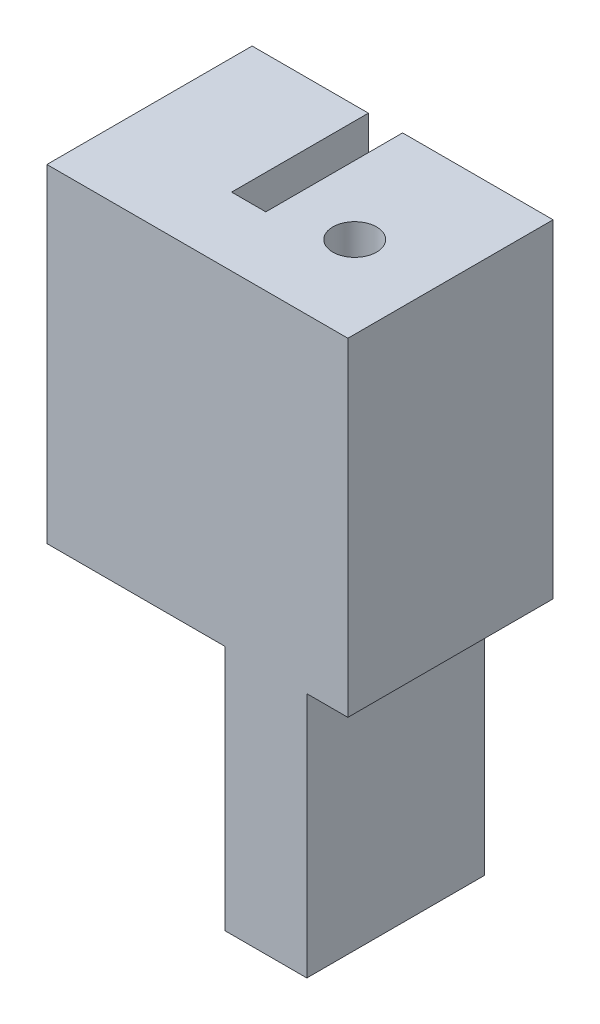
SolidWorks part; units mm, degrees
material "PET"
ref_plane "Front Plane" through (0, 0, 0) normal (0, 0, 1) x (1, 0, 0)
ref_plane "Top Plane" through (0, 0, 0) normal (0, 1, 0) x (1, 0, 0)
ref_plane "Right Plane" through (0, 0, 0) normal (1, 0, 0) x (0, 0, -1)
sketch "Sketch2" plane through (0, 0, 0) normal (0, 0, 1) x (1, 0, 0)
  line L0 (-26.5, 0) -> (-30.65, 0)
  line L1 (-26.5, 24) -> (-28.5, 24)
  line L2 (-26.5, 24) -> (-26.5, 0)
  line L4 (-28.5, 24) -> (-28.5, 6.0276)
  line L5 (-31, 24) -> (-39.5, 24)
  line L6 (-31, 24) -> (-31, 13.19)
  line L7 (-30.2, 5.5304) -> (-30.2, 11.6897)
  line L8 (-39.5, 24) -> (-39.5, 8.68)
  line L9 (-30.2, 11.6897) -> (-35.6851, 8.8877)
  line L10 (-31, 13.19) -> (-36.71, 10.2731)
  line L11 (-38.4927, 8.4496) -> (-39.5, 6.3626)
  line L12 (-39.5, 6.3626) -> (-39.5, 8.68)
  line L13 (-31.0158, 1.1429) -> (-32.6182, 0)
  line L14 (-32.6182, 0) -> (-30.65, 0)
  arc A1 (-31.0158, 1.1429) -> (-28.5, 6.0276) centre (-34.5, 6.0276) ccw
  arc A3 (-36.71, 10.2731) -> (-38.4927, 8.4496) centre (-34.8903, 6.711) ccw
  arc A4 (-35.6851, 8.8877) -> (-30.2, 5.5304) centre (-33.97, 5.5304) ccw
  dimension "D4" = 35.499
  dimension "D5" = 12
  dimension "D10" = 25.764
  dimension "D13" = 8
  dimension "D12" = 7.54
  dimension "D1" = 2
  dimension "D2" = 24
  dimension "D3" = 4.15
  dimension "D6" = 8.5
  dimension "D7" = 10.81
  dimension "D8" = 2.5
  dimension "D9" = 15.32
  dimension "D11" = 5.71
  dimension "D14" = 1.7
  dimension "D15" = 1.7
  dimension "D16" = 2.3174
  dimension "D17" = 1.9682
extrude "Boss-Extrude1" add sketch "Sketch2" along normal blind 10
sketch "Sketch3" plane through (0, 0, 10) normal (0, 0, 1) x (1, 0, 0)
  line L0 (-32.6182, 0) -> (-26.5, 0) construction
  line L1 (-26.5, 24) -> (-39.5, 24)
  line L2 (-26.5, 24) -> (-26.5, 0)
  line L3 (-26.5, 0) -> (-39.5, 0)
  line L4 (-39.5, 24) -> (-39.5, 0)
  line L5 (-39.5, 24) -> (-39.5, 6.3626) construction
extrude "Boss-Extrude2" add sketch "Sketch3" along normal blind 5
sketch "Sketch4" plane through (0, 24, 0) normal (0, 1, 0) x (1, 0, 0)
  line L1 (-26.5, -15) -> (-20.5, -15)
  line L2 (-26.5, -15) -> (-26.5, -2)
  line L3 (-26.5, -2) -> (-20.5, -2)
  line L4 (-20.5, -15) -> (-20.5, -2)
  dimension "D1" = 13
  dimension "D2" = 6
extrude "Boss-Extrude3" add sketch "Sketch4" against normal blind 42
sketch "Sketch5" plane through (0, 0, 2) normal (0, 0, -1) x (-1, 0, 0)
  line L1 (26.5, 0) -> (20.5, 0)
  line L2 (26.5, 0) -> (26.5, 24)
  line L3 (26.5, 24) -> (20.5, 24)
  line L4 (20.5, 0) -> (20.5, 24)
extrude "Boss-Extrude4" add sketch "Sketch5" along normal up to surface (2 mm away) up to face at (-28.8403, 9.1443, 0)
sketch "Sketch6" plane through (0, -18, 0) normal (0, -1, 0) x (1, 0, 0)
  line L0 (-26.5, 15) -> (-20.5, 2) construction
  circle A0 centre (-23.5, 8.5) radius 1.6
  point P6 (0, 0)
  dimension "D1" = 3.2
extrude "Cut-Extrude1" cut sketch "Sketch6" against normal through all
sketch "Sketch7" plane through (0, 0, 0) normal (0, 0, -1) x (-1, 0, 0)
  line L0 (26.5, 0) -> (26.5, 6.2712) construction
  line L1 (20.625, 2) -> (26.375, 2)
  line L2 (20.625, 2) -> (20.625, 4.65)
  line L3 (20.625, 4.65) -> (26.375, 4.65)
  line L4 (26.375, 2) -> (26.375, 4.65)
  line L5 (23.5, 4.65) -> (23.5, 2) construction
  line L7 (20.5, 0) -> (20.5, 24) construction
  line L8 (20.5, 5.4898) -> (26.5, 5.4898) construction
  line L9 (32.6182, 0) -> (20.5, 0) construction
  point P13 (23.5, 5.4898)
  point P14 (0, 0)
  dimension "D1" = 2.65
  dimension "D2" = 5.75
  dimension "D3" = 2
sketch "Sketch8" plane through (-20.5, 0, 0) normal (1, 0, 0) x (0, 0, -1)
  line L1 (0, 0) -> (-15, 0)
  line L2 (0, 0) -> (0, 24)
  line L3 (0, 24) -> (-15, 24)
  line L4 (-15, 0) -> (-15, 24)
extrude "Boss-Extrude5" add sketch "Sketch8" along normal blind 3
extrude "Cut-Extrude2" cut sketch "Sketch7" against normal blind 12.5
